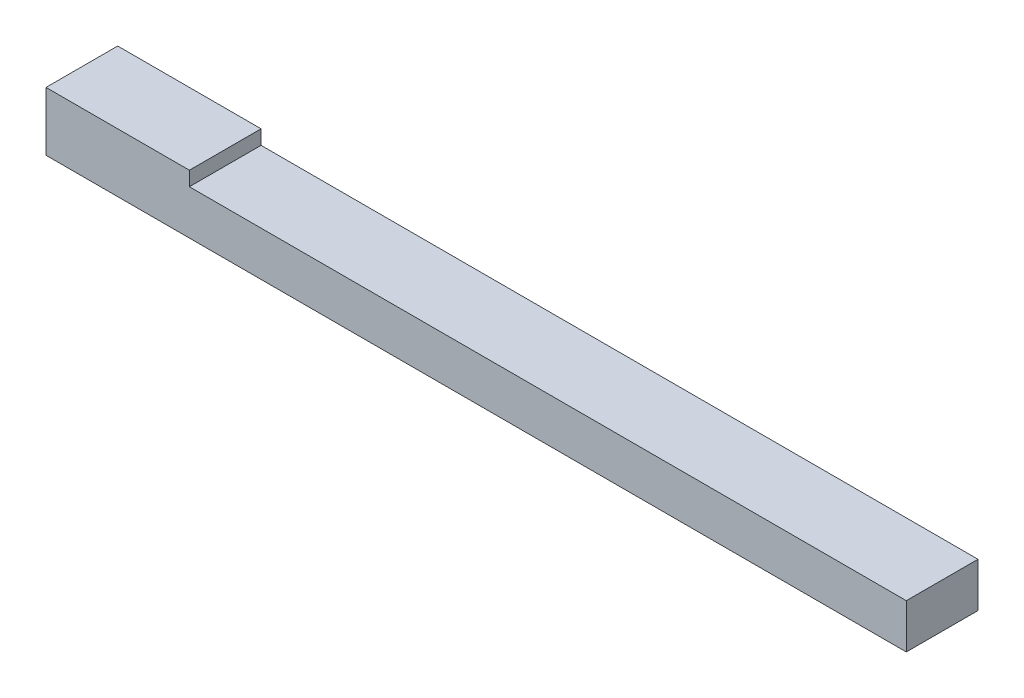
SolidWorks part; units mm, degrees
ref_plane "前视基准面" through (0, 0, 0) normal (0, 0, 1) x (1, 0, 0)
ref_plane "上视基准面" through (0, 0, 0) normal (0, 1, 0) x (1, 0, 0)
ref_plane "右视基准面" through (0, 0, 0) normal (1, 0, 0) x (0, 0, -1)
other "Configuration Table"
sketch "草图1" plane through (0, 0, 0) normal (0, 1, 0) x (1, 0, 0)
  line L1 (0, 0) -> (-120, 0)
  line L2 (0, 0) -> (0, 10)
  line L3 (0, 10) -> (-120, 10)
  line L4 (-120, 0) -> (-120, 10)
  dimension "D1" = 120
  dimension "D2" = 10
extrude "凸台-拉伸1" add sketch "草图1" along normal blind 6.2
sketch "草图5" plane through (0, 6.2, 0) normal (0, 1, 0) x (1, 0, 0)
  line L0 (-120, 0) -> (0, 0) construction
  line L6 (-120, 10) -> (-100, 10)
  line L7 (-120, 10) -> (-120, 0)
  line L8 (-120, 0) -> (-100, 0)
  line L9 (-100, 10) -> (-100, 0)
  dimension "D2" = 20
extrude "凸台-拉伸3" add sketch "草图5" along normal blind 2
